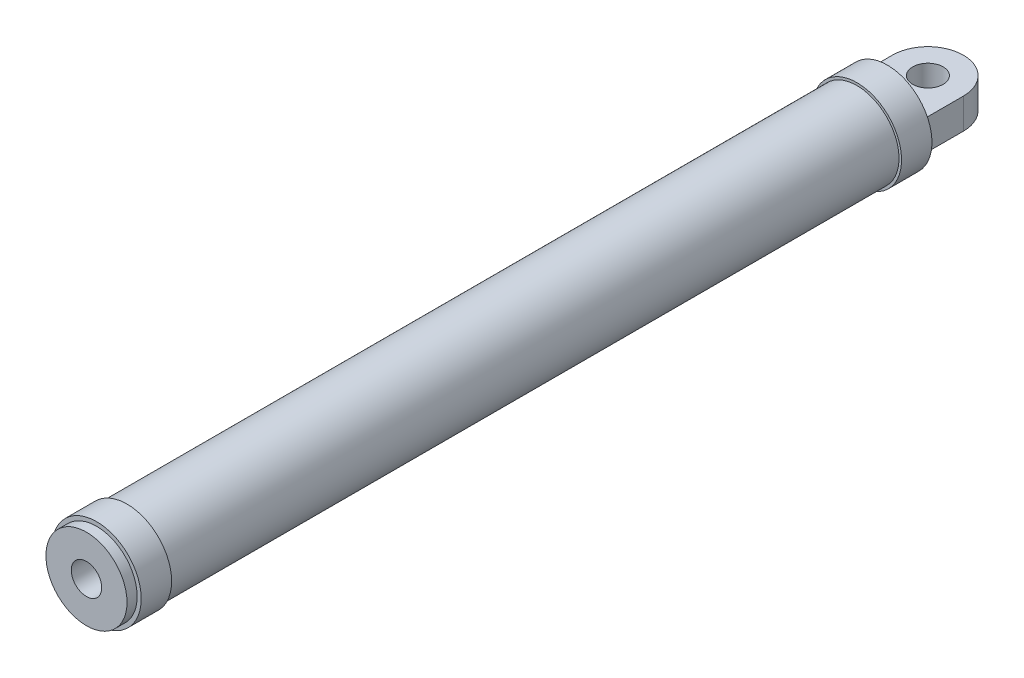
SolidWorks part; units mm, degrees
material "铸造合金钢"
ref_plane "前视基准面" through (0, 0, 0) normal (0, 0, 1) x (1, 0, 0)
ref_plane "上视基准面" through (0, 0, 0) normal (0, 1, 0) x (1, 0, 0)
ref_plane "右视基准面" through (0, 0, 0) normal (1, 0, 0) x (0, 0, -1)
sketch "草图1" plane through (0, 0, 0) normal (0, 0, 1) x (1, 0, 0)
  circle A0 centre (0, 0) radius 41.5
  dimension "D1" = 83
extrude "拉伸1" add sketch "草图1" along normal blind 720
sketch "草图2" plane through (0, 0, 720) normal (0, 0, 1) x (1, 0, 0)
  circle A0 centre (0, 0) radius 44
  dimension "D1" = 88
extrude "拉伸2" add sketch "草图2" along normal blind 30
sketch "草图3" plane through (0, 0, 0) normal (0, 0, -1) x (-1, 0, 0)
  circle A0 centre (0, 0) radius 44
  dimension "D1" = 88
extrude "拉伸3" add sketch "草图3" along normal blind 30
sketch "草图4" plane through (0, 0, 750) normal (0, 0, 1) x (1, 0, 0)
  circle A0 centre (0, 0) radius 40
  dimension "D1" = 80
extrude "拉伸4" add sketch "草图4" along normal blind 10
sketch "草图6" plane through (0, 0, 0) normal (0, 1, 0) x (1, 0, 0)
  line L0 (0, 30) -> (0, 110) construction
  line L1 (44, 30) -> (-44, 30) construction
  line L2 (-35, 70) -> (-35, 30)
  line L3 (-35, 30) -> (35, 30)
  line L4 (35, 30) -> (35, 70)
  circle A0 centre (0, 70) radius 15
  arc A1 (35, 70) -> (-35, 70) centre (0, 70) ccw
  dimension "D1" = 30
  dimension "D2" = 70
  dimension "D3" = 40
extrude "拉伸6" add sketch "草图6" along normal mid plane 30
sketch "草图5" plane through (0, 0, 760) normal (0, 0, 1) x (1, 0, 0)
  circle A0 centre (0, 0) radius 15
  dimension "D1" = 30
extrude "切除-拉伸1" cut sketch "草图5" against normal blind 220
ref_plane "基准面1" through (0, 0, -70) normal (0, 0, -1) x (-1, 0, 0)
